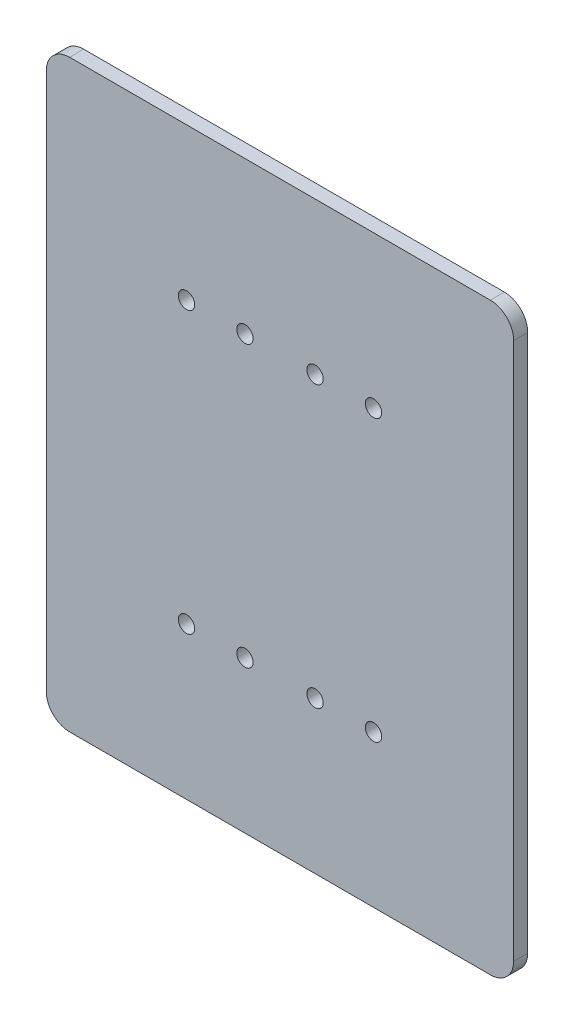
SolidWorks part; units mm, degrees
ref_plane "Front Plane" through (0, 0, 0) normal (0, 0, 1) x (1, 0, 0)
ref_plane "Top Plane" through (0, 0, 0) normal (0, 1, 0) x (1, 0, 0)
ref_plane "Right Plane" through (0, 0, 0) normal (1, 0, 0) x (0, 0, -1)
sketch "Sketch1" plane through (0, 0, 0) normal (0, 0, 1) x (1, 0, 0)
  line L0 (100, 250) -> (100, 0) construction
  line L1 (0, 0) -> (200, 0)
  line L2 (0, 0) -> (0, 250)
  line L3 (0, 250) -> (200, 250)
  line L4 (200, 0) -> (200, 250)
  dimension "D6" = 250
  dimension "14" = 200
extrude "Boss-Extrude1" add sketch "Sketch1" along normal blind 6
sketch "Sketch2" plane through (0, 0, 0) normal (0, 0, -1) x (-1, 0, 0)
  line L0 (-100, 0) -> (-100, 250) construction
  line L1 (0, 0) -> (-200, 0) construction
  line L2 (-200, 250) -> (0, 250) construction
  line L3 (-200, 125) -> (0, 125) construction
  line L4 (-200, 0) -> (-200, 250) construction
  line L5 (0, 250) -> (0, 0) construction
  line L12 (-140, 0) -> (-140, 250) construction
  line L13 (-60, 0) -> (-60, 250) construction
  line L14 (-200, 65) -> (0, 65) construction
  line L15 (-200, 185) -> (0, 185) construction
  circle A1 centre (-60, 65) radius 3.5
  circle A2 centre (-85, 65) radius 3.5
  circle A3 centre (-140, 65) radius 3.5
  circle A4 centre (-115, 65) radius 3.5
  circle A5 centre (-140, 185) radius 3.5
  circle A6 centre (-115, 185) radius 3.5
  circle A7 centre (-85, 185) radius 3.5
  circle A8 centre (-60, 185) radius 3.5
  dimension "D7" = 7
  dimension "D8" = 60
  dimension "D9" = 60
  dimension "D10" = 60
  dimension "D11" = 25
  dimension "D2" = 25
  dimension "D12" = 25
  dimension "D13" = 25
  dimension "D14" = 60
  dimension "D3" = 40
  dimension "D4" = 40
  dimension "D5" = 60
  dimension "D6" = 60
extrude "Cut-Extrude1" cut sketch "Sketch2" against normal up to surface (6 mm away) up to face at (100, 125, 6)
fillet "Fillet1" radius 10 4 edges at (0, 250, 3) (200, 250, 3) (200, 0, 3) (0, 0, 3)
